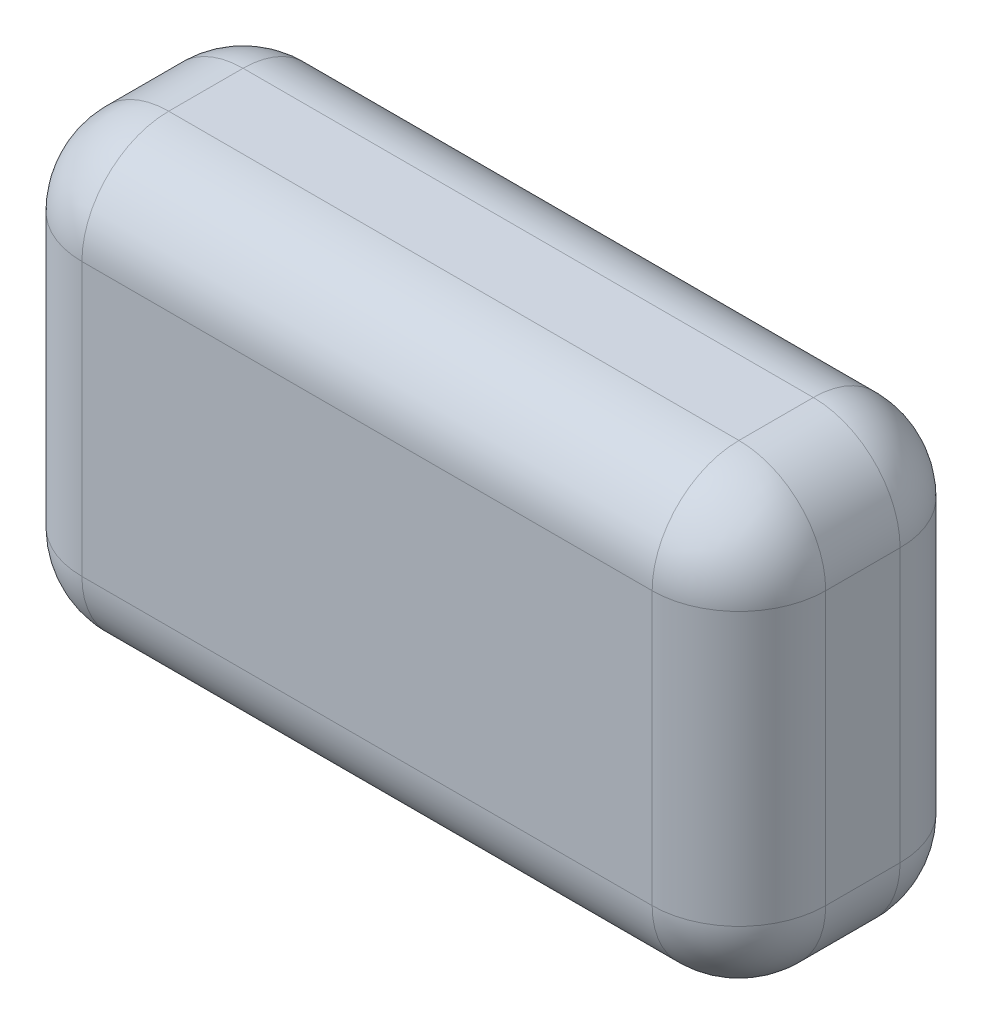
SolidWorks part; units mm, degrees
ref_plane "Front Plane" through (0, 0, 0) normal (0, 0, 1) x (1, 0, 0)
ref_plane "Top Plane" through (0, 0, 0) normal (0, 1, 0) x (1, 0, 0)
ref_plane "Right Plane" through (0, 0, 0) normal (1, 0, 0) x (0, 0, -1)
sketch "Sketch1" plane through (0, 0, 0) normal (0, 0, 1) x (1, 0, 0)
  line L1 (-381, 228.6) -> (381, 228.6)
  line L2 (-381, 228.6) -> (-381, -228.6)
  line L3 (-381, -228.6) -> (381, -228.6)
  line L4 (381, 228.6) -> (381, -228.6)
  line L5 (-381, 228.6) -> (381, -228.6) construction
  line L6 (-381, -228.6) -> (381, 228.6) construction
  point P0 (0, 0)
  dimension "D1" = 457.2
  dimension "D2" = 762
extrude "Boss-Extrude1" add sketch "Sketch1" along normal mid plane 254
fillet "Fillet1" radius 88.9 12 edges at (-381, 228.6, 0) (0, 228.6, -127) (-381, 0, -127) (0, -228.6, -127) (381, -228.6, 0) (381, 228.6, 0) (381, 0, -127) (0, -228.6, 127) (-381, 0, 127) (0, 228.6, 127) (381, 0, 127) (-381, -228.6, 0)
